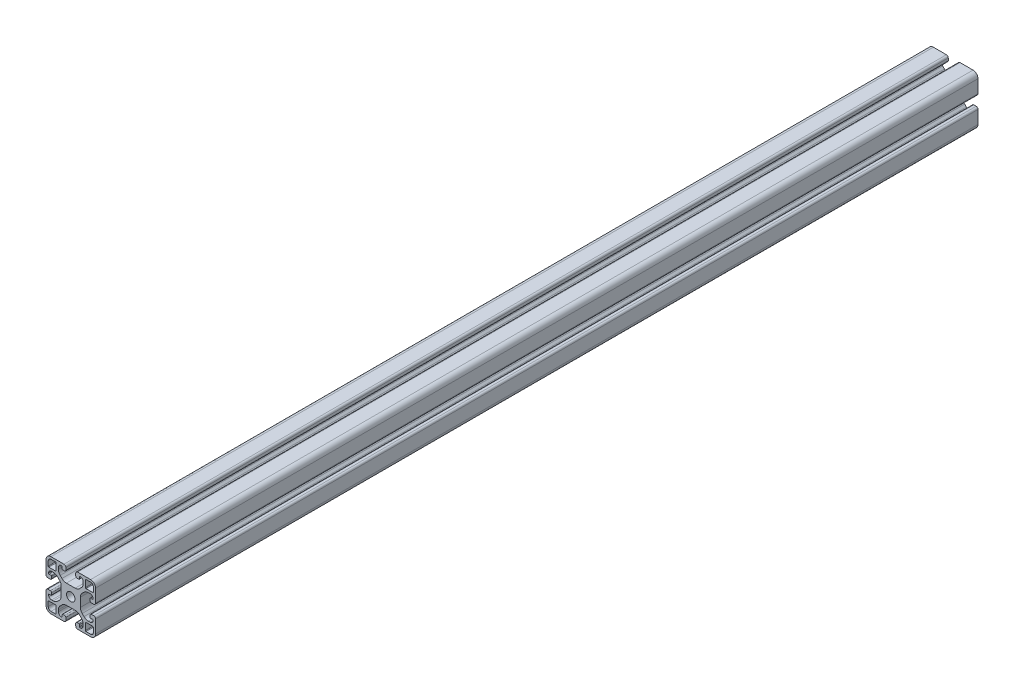
SolidWorks part; units mm, degrees
ref_plane "Plan de face" through (0, 0, 0) normal (0, 0, 1) x (1, 0, 0)
ref_plane "Plan de dessus" through (0, 0, 0) normal (0, 1, 0) x (1, 0, 0)
ref_plane "Plan de droite" through (0, 0, 0) normal (1, 0, 0) x (0, 0, -1)
ref_plane "Plan1" through (0, 0, -30) normal (0, 0, -1) x (-1, 0, 0)
sketch "Esquisse1" plane through (0, 0, -30) normal (0, 0, -1) x (-1, 0, 0)
  line L0 (-4.5, 15) -> (-4.5, 13.5)
  line L1 (-4, 13) -> (-2.5, 13)
  line L2 (-4.5, 10) -> (-5.8076, 10)
  line L3 (-9.3431, 11.4645) -> (-10.7855, 12.9069)
  line L4 (-12.25, 16.4424) -> (-12.25, 23.5576)
  line L5 (-10.7855, 27.0931) -> (-9.3431, 28.5355)
  line L6 (-5.8076, 30) -> (-4.5, 30)
  line L7 (-2.5, 27) -> (-4, 27)
  line L8 (-4.5, 26.5) -> (-4.5, 25)
  line L9 (-3.5, 24) -> (-1.5, 24)
  line L10 (0, 25.5) -> (0, 36)
  line L11 (-4, 40) -> (-14.5, 40)
  line L12 (-16, 38.5) -> (-16, 36.5)
  line L13 (-15, 35.5) -> (-13.5, 35.5)
  line L14 (-13, 36) -> (-13, 37.5)
  line L15 (-10, 35.5) -> (-10, 34.1924)
  line L16 (-11.4645, 30.6569) -> (-12.9069, 29.2145)
  line L17 (-16.4424, 27.75) -> (-23.5576, 27.75)
  line L18 (-27.0931, 29.2145) -> (-28.5355, 30.6569)
  line L19 (-30, 34.1924) -> (-30, 35.5)
  line L20 (-27, 37.5) -> (-27, 36)
  line L21 (-26.5, 35.5) -> (-25, 35.5)
  line L22 (-24, 36.5) -> (-24, 38.5)
  line L23 (-25.5, 40) -> (-36, 40)
  line L24 (-40, 36) -> (-40, 25.5)
  line L25 (-38.5, 24) -> (-36.5, 24)
  line L26 (-35.5, 25) -> (-35.5, 26.5)
  line L27 (-36, 27) -> (-37.5, 27)
  line L28 (-35.5, 30) -> (-34.1924, 30)
  line L29 (-30.6569, 28.5355) -> (-29.2145, 27.0931)
  line L30 (-27.75, 23.5576) -> (-27.75, 16.4424)
  line L31 (-29.2145, 12.9069) -> (-30.6569, 11.4645)
  line L32 (-34.1924, 10) -> (-35.5, 10)
  line L33 (-37.5, 13) -> (-36, 13)
  line L34 (-35.5, 13.5) -> (-35.5, 15)
  line L35 (-36.5, 16) -> (-38.5, 16)
  line L36 (-40, 14.5) -> (-40, 4)
  line L37 (-36, 0) -> (-25.5, 0)
  line L38 (-24, 1.5) -> (-24, 3.5)
  line L39 (-25, 4.5) -> (-26.5, 4.5)
  line L40 (-27, 4) -> (-27, 2.5)
  line L41 (-30, 4.5) -> (-30, 5.8076)
  line L42 (-28.5355, 9.3431) -> (-27.0931, 10.7855)
  line L43 (-23.5576, 12.25) -> (-16.4424, 12.25)
  line L44 (-12.9069, 10.7855) -> (-11.4645, 9.3431)
  line L45 (-10, 5.8076) -> (-10, 4.5)
  line L46 (-13, 2.5) -> (-13, 4)
  line L47 (-13.5, 4.5) -> (-15, 4.5)
  line L48 (-16, 3.5) -> (-16, 1.5)
  line L49 (-14.5, 0) -> (-4, 0)
  line L50 (0, 4) -> (0, 14.5)
  line L51 (-1.5, 16) -> (-3.5, 16)
  line L52 (-4, 1.8) -> (-7.7, 1.8)
  line L53 (-8.2, 2.3) -> (-8.2, 7.7)
  line L54 (-7.7, 8.2) -> (-2.3, 8.2)
  line L55 (-1.8, 7.7) -> (-1.8, 4)
  line L56 (-38.2, 4) -> (-38.2, 7.7)
  line L57 (-37.7, 8.2) -> (-32.3, 8.2)
  line L58 (-31.8, 7.7) -> (-31.8, 2.3)
  line L59 (-32.3, 1.8) -> (-36, 1.8)
  line L60 (-36, 38.2) -> (-32.3, 38.2)
  line L61 (-31.8, 37.7) -> (-31.8, 32.3)
  line L62 (-32.3, 31.8) -> (-37.7, 31.8)
  line L63 (-38.2, 32.3) -> (-38.2, 36)
  line L64 (-1.8, 36) -> (-1.8, 32.3)
  line L65 (-2.3, 31.8) -> (-7.7, 31.8)
  line L66 (-8.2, 32.3) -> (-8.2, 37.7)
  line L67 (-7.7, 38.2) -> (-4, 38.2)
  arc A0 (-4.5, 13.5) -> (-4, 13) centre (-4, 13.5) ccw
  arc A1 (-2.5, 13) -> (-2, 12.5) centre (-2.5, 12.5) cw
  arc A2 (-2, 12.5) -> (-4.5, 10) centre (-4.5, 12.5) cw
  arc A3 (-5.8076, 10) -> (-9.3431, 11.4645) centre (-5.8076, 15) cw
  arc A4 (-10.7855, 12.9069) -> (-12.25, 16.4424) centre (-7.25, 16.4424) cw
  arc A5 (-12.25, 23.5576) -> (-10.7855, 27.0931) centre (-7.25, 23.5576) cw
  arc A6 (-9.3431, 28.5355) -> (-5.8076, 30) centre (-5.8076, 25) cw
  arc A7 (-4.5, 30) -> (-2, 27.5) centre (-4.5, 27.5) cw
  arc A8 (-2, 27.5) -> (-2.5, 27) centre (-2.5, 27.5) cw
  arc A9 (-4, 27) -> (-4.5, 26.5) centre (-4, 26.5) ccw
  arc A10 (-4.5, 25) -> (-3.5, 24) centre (-3.5, 25) ccw
  arc A11 (-1.5, 24) -> (0, 25.5) centre (-1.5, 25.5) ccw
  arc A12 (0, 36) -> (-4, 40) centre (-4, 36) ccw
  arc A13 (-14.5, 40) -> (-16, 38.5) centre (-14.5, 38.5) ccw
  arc A14 (-16, 36.5) -> (-15, 35.5) centre (-15, 36.5) ccw
  arc A15 (-13.5, 35.5) -> (-13, 36) centre (-13.5, 36) ccw
  arc A16 (-13, 37.5) -> (-12.5, 38) centre (-12.5, 37.5) cw
  arc A17 (-12.5, 38) -> (-10, 35.5) centre (-12.5, 35.5) cw
  arc A18 (-10, 34.1924) -> (-11.4645, 30.6569) centre (-15, 34.1924) cw
  arc A19 (-12.9069, 29.2145) -> (-16.4424, 27.75) centre (-16.4424, 32.75) cw
  arc A20 (-23.5576, 27.75) -> (-27.0931, 29.2145) centre (-23.5576, 32.75) cw
  arc A21 (-28.5355, 30.6569) -> (-30, 34.1924) centre (-25, 34.1924) cw
  arc A22 (-30, 35.5) -> (-27.5, 38) centre (-27.5, 35.5) cw
  arc A23 (-27.5, 38) -> (-27, 37.5) centre (-27.5, 37.5) cw
  arc A24 (-27, 36) -> (-26.5, 35.5) centre (-26.5, 36) ccw
  arc A25 (-25, 35.5) -> (-24, 36.5) centre (-25, 36.5) ccw
  arc A26 (-24, 38.5) -> (-25.5, 40) centre (-25.5, 38.5) ccw
  arc A27 (-36, 40) -> (-40, 36) centre (-36, 36) ccw
  arc A28 (-40, 25.5) -> (-38.5, 24) centre (-38.5, 25.5) ccw
  arc A29 (-36.5, 24) -> (-35.5, 25) centre (-36.5, 25) ccw
  arc A30 (-35.5, 26.5) -> (-36, 27) centre (-36, 26.5) ccw
  arc A31 (-37.5, 27) -> (-38, 27.5) centre (-37.5, 27.5) cw
  arc A32 (-38, 27.5) -> (-35.5, 30) centre (-35.5, 27.5) cw
  arc A33 (-34.1924, 30) -> (-30.6569, 28.5355) centre (-34.1924, 25) cw
  arc A34 (-29.2145, 27.0931) -> (-27.75, 23.5576) centre (-32.75, 23.5576) cw
  arc A35 (-27.75, 16.4424) -> (-29.2145, 12.9069) centre (-32.75, 16.4424) cw
  arc A36 (-30.6569, 11.4645) -> (-34.1924, 10) centre (-34.1924, 15) cw
  arc A37 (-35.5, 10) -> (-38, 12.5) centre (-35.5, 12.5) cw
  arc A38 (-38, 12.5) -> (-37.5, 13) centre (-37.5, 12.5) cw
  arc A39 (-36, 13) -> (-35.5, 13.5) centre (-36, 13.5) ccw
  arc A40 (-35.5, 15) -> (-36.5, 16) centre (-36.5, 15) ccw
  arc A41 (-38.5, 16) -> (-40, 14.5) centre (-38.5, 14.5) ccw
  arc A42 (-40, 4) -> (-36, 0) centre (-36, 4) ccw
  arc A43 (-25.5, 0) -> (-24, 1.5) centre (-25.5, 1.5) ccw
  arc A44 (-24, 3.5) -> (-25, 4.5) centre (-25, 3.5) ccw
  arc A45 (-26.5, 4.5) -> (-27, 4) centre (-26.5, 4) ccw
  arc A46 (-27, 2.5) -> (-27.5, 2) centre (-27.5, 2.5) cw
  arc A47 (-27.5, 2) -> (-30, 4.5) centre (-27.5, 4.5) cw
  arc A48 (-30, 5.8076) -> (-28.5355, 9.3431) centre (-25, 5.8076) cw
  arc A49 (-27.0931, 10.7855) -> (-23.5576, 12.25) centre (-23.5576, 7.25) cw
  arc A50 (-16.4424, 12.25) -> (-12.9069, 10.7855) centre (-16.4424, 7.25) cw
  arc A51 (-11.4645, 9.3431) -> (-10, 5.8076) centre (-15, 5.8076) cw
  arc A52 (-10, 4.5) -> (-12.5, 2) centre (-12.5, 4.5) cw
  arc A53 (-12.5, 2) -> (-13, 2.5) centre (-12.5, 2.5) cw
  arc A54 (-13, 4) -> (-13.5, 4.5) centre (-13.5, 4) ccw
  arc A55 (-15, 4.5) -> (-16, 3.5) centre (-15, 3.5) ccw
  arc A56 (-16, 1.5) -> (-14.5, 0) centre (-14.5, 1.5) ccw
  arc A57 (-4, 0) -> (0, 4) centre (-4, 4) ccw
  arc A58 (0, 14.5) -> (-1.5, 16) centre (-1.5, 14.5) ccw
  arc A59 (-3.5, 16) -> (-4.5, 15) centre (-3.5, 15) ccw
  circle A60 centre (-20, 20) radius 3.4
  arc A61 (-1.8, 4) -> (-4, 1.8) centre (-4, 4) cw
  arc A62 (-7.7, 1.8) -> (-8.2, 2.3) centre (-7.7, 2.3) cw
  arc A63 (-8.2, 7.7) -> (-7.7, 8.2) centre (-7.7, 7.7) cw
  arc A64 (-2.3, 8.2) -> (-1.8, 7.7) centre (-2.3, 7.7) cw
  arc A65 (-36, 1.8) -> (-38.2, 4) centre (-36, 4) cw
  arc A66 (-38.2, 7.7) -> (-37.7, 8.2) centre (-37.7, 7.7) cw
  arc A67 (-32.3, 8.2) -> (-31.8, 7.7) centre (-32.3, 7.7) cw
  arc A68 (-31.8, 2.3) -> (-32.3, 1.8) centre (-32.3, 2.3) cw
  arc A69 (-38.2, 36) -> (-36, 38.2) centre (-36, 36) cw
  arc A70 (-32.3, 38.2) -> (-31.8, 37.7) centre (-32.3, 37.7) cw
  arc A71 (-31.8, 32.3) -> (-32.3, 31.8) centre (-32.3, 32.3) cw
  arc A72 (-37.7, 31.8) -> (-38.2, 32.3) centre (-37.7, 32.3) cw
  arc A73 (-4, 38.2) -> (-1.8, 36) centre (-4, 36) cw
  arc A74 (-1.8, 32.3) -> (-2.3, 31.8) centre (-2.3, 32.3) cw
  arc A75 (-7.7, 31.8) -> (-8.2, 32.3) centre (-7.7, 32.3) cw
  arc A76 (-8.2, 37.7) -> (-7.7, 38.2) centre (-7.7, 37.7) cw
extrude "Boss.-Extru.1" add sketch "Esquisse1" against normal blind 712
